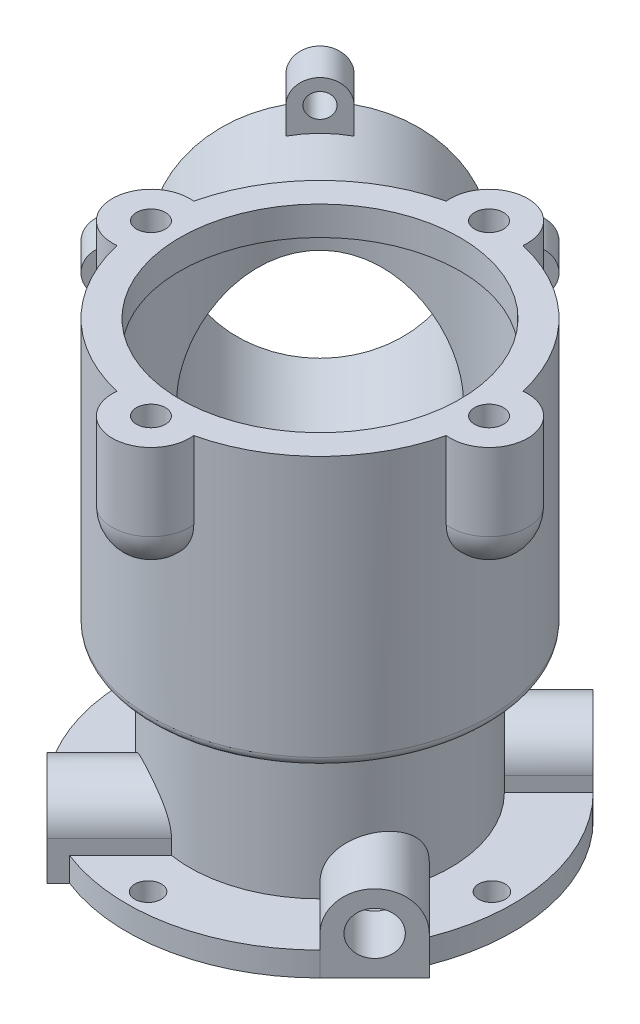
SolidWorks part; units mm, degrees
ref_plane "前视基准面" through (0, 0, 0) normal (0, 0, 1) x (1, 0, 0)
ref_plane "上视基准面" through (0, 0, 0) normal (0, 1, 0) x (1, 0, 0)
ref_plane "右视基准面" through (0, 0, 0) normal (1, 0, 0) x (0, 0, -1)
sketch "草图1" plane through (0, 0, 0) normal (0, 0, 1) x (1, 0, 0)
  line L0 (0, 0) -> (0, 93.1027) construction
  line L1 (-40, 0) -> (-22.5, 0)
  line L2 (-40, 0) -> (-40, 5)
  line L3 (-40, 5) -> (-27, 5)
  line L4 (-27, 5) -> (-27, 34)
  line L5 (-27, 34) -> (-33, 34)
  line L6 (-35, 36) -> (-35, 90)
  line L7 (-35, 90) -> (-29, 90)
  line L8 (-30, 84) -> (-30, 39)
  line L9 (-30, 39) -> (-22.5, 39)
  line L10 (-22.5, 39) -> (-22.5, 0)
  line L11 (-30, 84) -> (-29, 84)
  line L12 (-29, 84) -> (-29, 90)
  arc A0 (-35, 36) -> (-33, 34) centre (-33, 36) ccw
  dimension "D12" = 2
  dimension "D1" = 90
  dimension "D2" = 22.5
  dimension "D3" = 27
  dimension "D4" = 5
  dimension "D5" = 5
  dimension "D6" = 5
  dimension "D7" = 56
  dimension "D8" = 29
  dimension "D9" = 6
  dimension "D10" = 30
  dimension "D11" = 40
revolve "旋转1" add sketch "草图1" angle 360 about L0
sketch "草图6" plane through (0, 0, 0) normal (0, 0, 1) x (1, 0, 0)
  line L1 (-38, 90) -> (-43, 90)
  line L2 (-38, 74) -> (-38, 90)
  line L3 (-43, 74) -> (-43, 90)
  line L5 (-38, 74) -> (-35, 74)
  line L6 (-35, 66) -> (-35, 74) construction
  line L8 (-35, 66) -> (-35, 74)
  arc A0 (-43, 74) -> (-35, 66) centre (-35, 74) ccw
  dimension "D1" = 16
revolve "旋转2" add sketch "草图6" angle 360 about L6
sketch "草图7" plane through (0, 90, 0) normal (0, 1, 0) x (1, 0, 0)
  circle A0 centre (-35, 0) radius 3
  arc A1 (-34.8714, 2.9972) -> (-34.8714, -2.9972) centre (0, 0) ccw construction
extrude "切除-拉伸2" cut sketch "草图7" against normal blind 16
pattern_circular "阵列(圆周)2" count 4 over 360 about axis through (0, 0, 0) along (0, 1, 0) of "旋转2"
pattern_circular "阵列(圆周)3" count 4 over 360 about axis through (0, 90, 0) along (0, -1, 0) of "切除-拉伸2"
sketch "草图8" plane through (0, 0, 0) normal (1, 0, 0) x (0, 0, -1)
  line L0 (-29, 90) -> (-29, 84)
  line L1 (-7.9476, 90) -> (-34.0857, 90) construction
  line L2 (-29, 84) -> (-30, 84)
  line L3 (-30, 84) -> (-30, 53.4)
  line L4 (-30, 53.4) -> (0, 53.4)
  line L5 (8, 90) -> (-8, 90) construction
  line L6 (8, 90) -> (-8, 90) construction
  line L7 (0, 90) -> (0, 53.4)
  line L8 (-29, 90) -> (0, 90)
  point P4 (0, 90)
  point P10 (0, 90)
  dimension "D1" = 29
  dimension "D2" = 30
  dimension "D3" = 6
revolve "切除-旋转3" cut sketch "草图8" angle 360 about L7
sketch "草图9" plane through (0, 90, 0) normal (0, 1, 0) x (1, 0, 0)
  line L0 (0, 35) -> (-35, 0) construction
  line L1 (-17.5, 17.5) -> (-40.5751, 40.5751) construction
ref_plane "基准面1" through (-17.5, 0, -17.5) normal (-0.7071, 0, -0.7071) x (-0.7071, 0, 0.7071)
ref_plane "基准面2" through (0, 0, 0) normal (-0.7071, 0, -0.7071) x (-0.7071, 0, 0.7071)
sketch "草图11" plane through (0, 0, 0) normal (-0.7071, 0, -0.7071) x (-0.7071, 0, 0.7071)
  line L0 (18.4824, 90) -> (-18.4824, 90) construction
  circle A0 centre (0, 60) radius 21
  circle A1 centre (0, 60) radius 25
  point P31 (0, 60)
  dimension "D1" = 42
  dimension "D2" = 30
extrude "凸台-拉伸2" add sketch "草图11" along normal blind 62
sketch "草图12" plane through (-43.8406, 0, -43.8406) normal (-0.7071, 0, -0.7071) x (-0.7071, 0, 0.7071)
  line L0 (-5, 90) -> (-5, 84.4949)
  line L1 (5, 90) -> (5, 84.4949)
  arc A0 (5, 84.4949) -> (-5, 84.4949) centre (0, 60) ccw
  circle A1 centre (0, 90) radius 2.5
  arc A2 (5, 90) -> (-5, 90) centre (0, 90) ccw
  dimension "D2" = 10
  dimension "D3" = 5
extrude "凸台-拉伸3" add sketch "草图12" against normal blind 8
pattern_circular "阵列(圆周)4" count 4 over 360 about axis through (0, 60, 0) along (-0.7071, 0, -0.7071) of "凸台-拉伸3"
sketch "草图13" plane through (-43.8406, 0, -43.8406) normal (-0.7071, 0, -0.7071) x (-0.7071, 0, 0.7071)
  circle A0 centre (0, 60) radius 21
extrude "切除-拉伸3" cut sketch "草图13" against normal blind 69
sketch "草图14" plane through (0, 0, 0) normal (0, 0, 1) x (1, 0, 0)
  line L0 (-29, 90) -> (-29, 84)
  line L1 (-7.9476, 90) -> (-34.0857, 90) construction
  line L2 (-29, 84) -> (-30, 84)
  line L3 (-30, 84) -> (-30, 39)
  line L4 (-30, 39) -> (-22.5, 39)
  line L5 (0, 90) -> (0, 39) construction
  line L6 (8, 90) -> (-8, 90) construction
  line L7 (-29, 90) -> (0, 90)
  line L8 (0, 90) -> (0, 39)
  line L9 (-22.5, 39) -> (-22.5, 5)
  line L10 (40, 5) -> (-40, 5) construction
  line L11 (-22.5, 5) -> (0, 5)
  line L12 (0, 5) -> (0, 39)
  dimension "D1" = 29
  dimension "D2" = 30
  dimension "D3" = 6
  dimension "D4" = 51
  dimension "D5" = 22.5
revolve "切除-旋转4" cut sketch "草图14" angle 360 about L5
sketch "草图15" plane through (0, 0, 0) normal (0, -1, 0) x (1, 0, 0)
  line L0 (0, 0) -> (-28.2843, -28.2843) construction
  circle A0 centre (0, 0) radius 40 construction
ref_plane "基准面3" through (-28.2843, 0, -28.2843) normal (-0.7071, 0, -0.7071) x (-0.7071, 0, 0.7071)
sketch "草图16" plane through (-28.2843, 0, -28.2843) normal (-0.7071, 0, -0.7071) x (-0.7071, 0, 0.7071)
  line L0 (-40, 0) -> (40, 0) construction
  line L1 (16, 8) -> (16, 0)
  line L2 (0, 0) -> (16, 0)
  line L3 (0, 8) -> (0, 0)
  arc A0 (16, 8) -> (0, 8) centre (8, 8) ccw
  dimension "D2" = 16
  dimension "D1" = 8
extrude "凸台-拉伸4" add sketch "草图16" against normal blind 35
sketch "草图17" plane through (-28.2843, 0, -28.2843) normal (-0.7071, 0, -0.7071) x (-0.7071, 0, 0.7071)
  point P0 (8, 8)
ref_plane "基准面4" through (0, 8, 0) normal (0, -1, 0) x (-1, 0, 0)
sketch "草图18" plane through (0, 8, 0) normal (0, -1, 0) x (-1, 0, 0)
  line L0 (33.9411, 22.6274) -> (6.5677, -4.746) construction
  line L1 (37.1231, 19.4454) -> (28.6378, 10.9602)
  line L2 (28.2843, 28.2843) -> (39.598, 16.9706) construction
  line L4 (28.6378, 10.9602) -> (26.4071, 11.5579)
  line L5 (0, 0) -> (28.2843, 28.2843) construction
  line L6 (8.3355, -6.5138) -> (26.4071, 11.5579)
  line L7 (6.5677, -4.746) -> (8.3355, -6.5138)
  line L8 (33.9411, 22.6274) -> (37.1231, 19.4454)
  line L9 (33.9411, 22.6274) -> (6.5677, -4.746)
  dimension "D1" = 4.5
  dimension "D2" = 12
  dimension "D4" = 8
  dimension "D5" = 60
  dimension "D6" = 2.5
revolve "切除-旋转5" cut sketch "草图18" angle 360 about L0
pattern_circular "阵列(圆周)5" count 4 over 360 about axis through (0, 0, 0) along (0, 1, 0) of "凸台-拉伸4", "切除-旋转5"
sketch "草图20" plane through (0, 0, 0) normal (0, -1, 0) x (1, 0, 0)
  circle A0 centre (0, 0) radius 22.5
extrude "切除-拉伸4" cut sketch "草图20" against normal blind 60
sketch "草图21" plane through (0, 0, 0) normal (0, -1, 0) x (1, 0, 0)
  circle A0 centre (0, -35.5966) radius 2.75
  dimension "D2" = 5.5
extrude "切除-拉伸5" cut sketch "草图21" against normal blind 12
pattern_circular "阵列(圆周)6" count 4 over 360 about axis through (0, 0, 0) along (0, 1, 0) of "切除-拉伸5"
